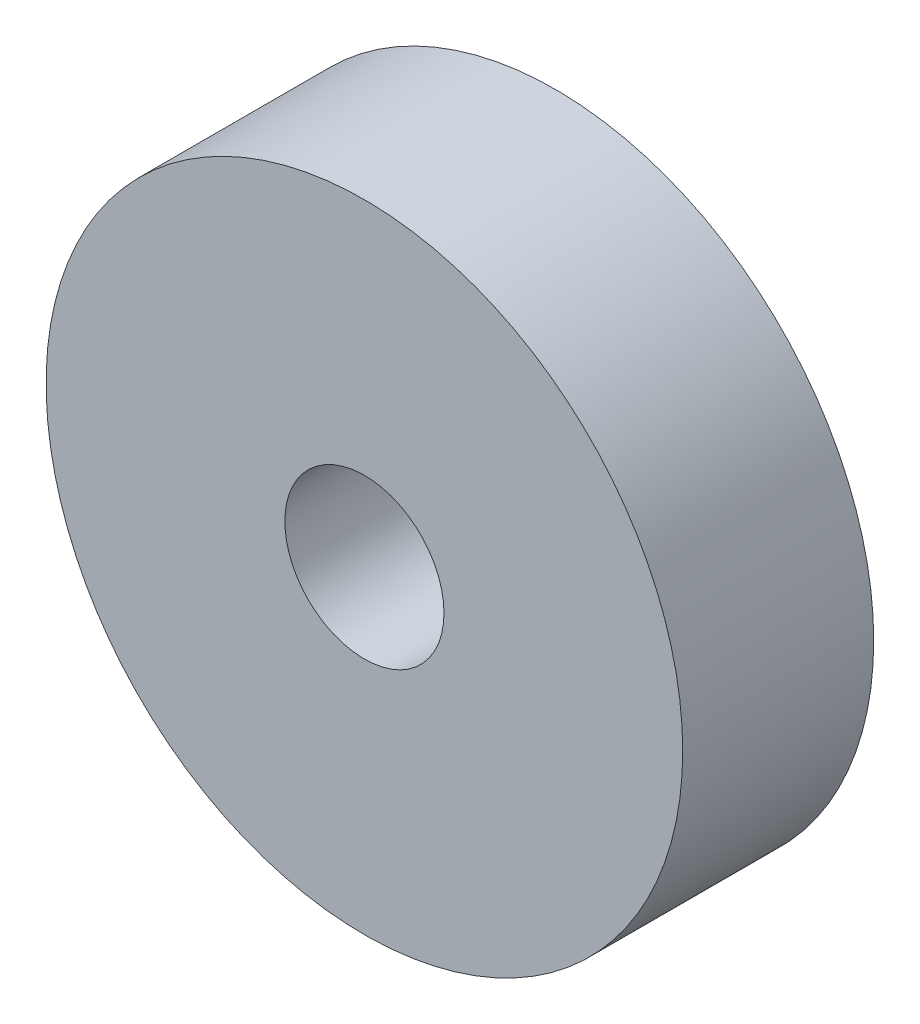
SolidWorks part; units mm, degrees
ref_plane "前视基准面" through (0, 0, 0) normal (0, 0, 1) x (1, 0, 0)
ref_plane "上视基准面" through (0, 0, 0) normal (0, 1, 0) x (1, 0, 0)
ref_plane "右视基准面" through (0, 0, 0) normal (1, 0, 0) x (0, 0, -1)
sketch "草图1" plane through (0, 0, 0) normal (0, 0, 1) x (1, 0, 0)
  circle A0 centre (0, 0) radius 5
  dimension "D1" = 10
extrude "凸台-拉伸1" add sketch "草图1" along normal blind 3
sketch "草图2" plane through (0, 0, 3) normal (0, 0, 1) x (1, 0, 0)
  circle A0 centre (0, 0) radius 1.25
  dimension "D1" = 2.5
extrude "切除-拉伸1" cut sketch "草图2" against normal blind 8
cosmetic thread "装饰螺纹线1"
